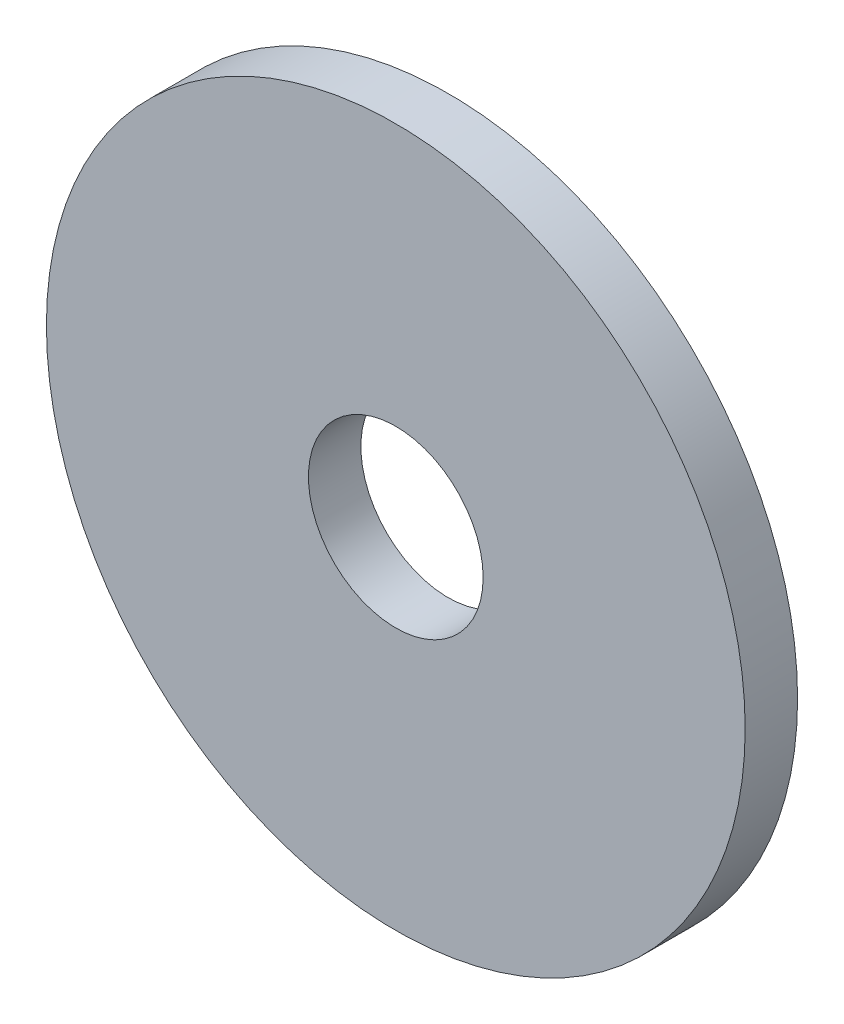
SolidWorks part; units mm, degrees
ref_plane "Front Plane" through (0, 0, 0) normal (0, 0, 1) x (1, 0, 0)
ref_plane "Top Plane" through (0, 0, 0) normal (0, 1, 0) x (1, 0, 0)
ref_plane "Right Plane" through (0, 0, 0) normal (1, 0, 0) x (0, 0, -1)
sketch "Sketch1" plane through (0, 0, 0) normal (0, 0, 1) x (1, 0, 0)
  circle A0 centre (45, -11.5) radius 20
  circle A1 centre (45, -11.5) radius 5
  dimension "D1" = 40
  dimension "D2" = 10
extrude "Boss-Extrude1" add sketch "Sketch1" against normal blind 3
